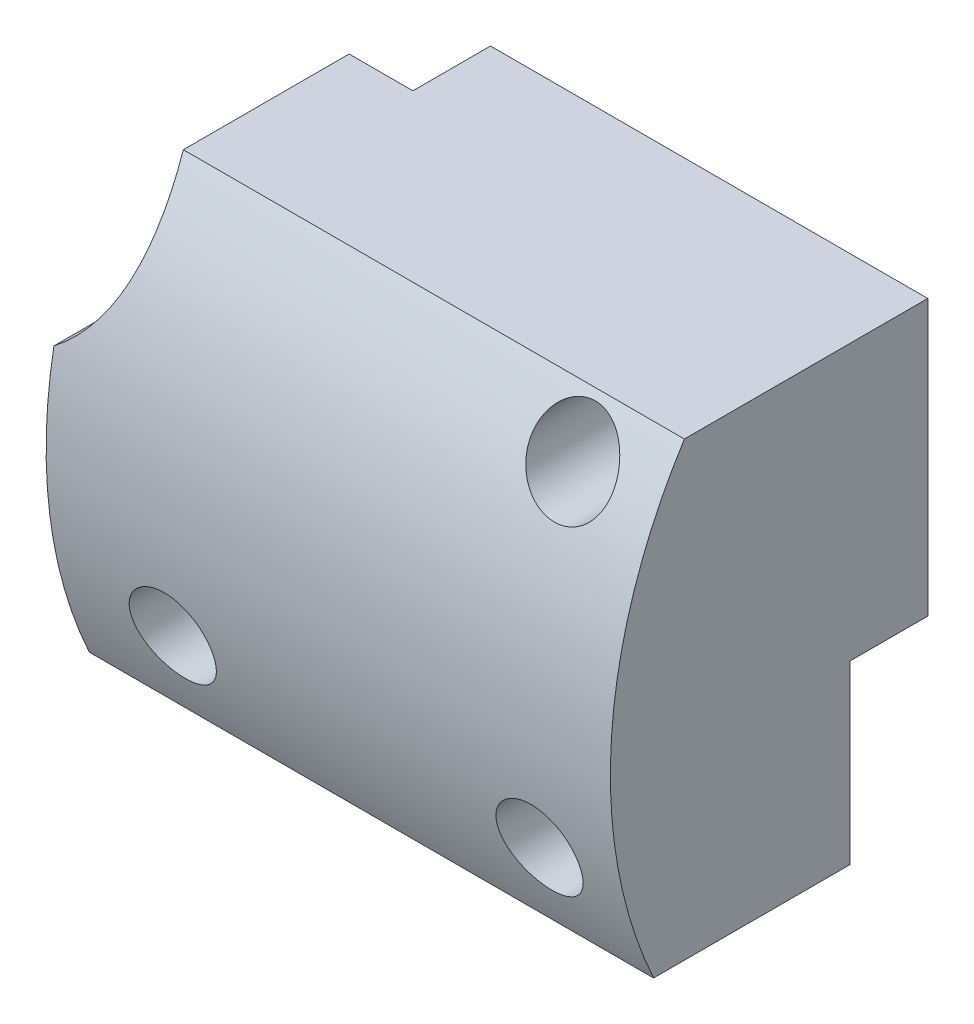
SolidWorks part; units mm, degrees
ref_plane "Front Plane" through (0, 0, 0) normal (0, 0, 1) x (1, 0, 0)
ref_plane "Top Plane" through (0, 0, 0) normal (0, 1, 0) x (1, 0, 0)
ref_plane "Right Plane" through (0, 0, 0) normal (1, 0, 0) x (0, 0, -1)
sketch "Sketch1" plane through (0, 0, 0) normal (0, 0, 1) x (1, 0, 0)
  line L1 (-21.3443, 32.2851) -> (-61.3443, 32.2851)
  line L2 (-21.3443, 32.2851) -> (-21.3443, 64.2851)
  line L3 (-21.3443, 64.2851) -> (-61.3443, 64.2851)
  line L4 (-61.3443, 32.2851) -> (-61.3443, 64.2851)
  dimension "D1" = 40
  dimension "D2" = 32
extrude "Boss-Extrude1" add sketch "Sketch1" along normal blind 17
sketch "Sketch3" plane through (0, 0, 0) normal (0, 0, -1) x (-1, 0, 0)
  line L1 (21.3443, 64.2851) -> (52.3443, 64.2851)
  line L2 (21.3443, 64.2851) -> (21.3443, 44.7851)
  line L3 (21.3443, 44.7851) -> (52.3443, 44.7851)
  line L4 (52.3443, 64.2851) -> (52.3443, 44.7851)
  dimension "D1" = 31
  dimension "D2" = 19.5
extrude "Boss-Extrude2" add sketch "Sketch3" along normal blind 5.5
sketch "Sketch2" plane through (0, 0, 17) normal (0, 0, 1) x (1, 0, 0)
  line L0 (-21.3443, 60.7851) -> (-61.3443, 60.7851) construction
  line L1 (-21.3443, 32.2851) -> (-21.3443, 64.2851) construction
  line L2 (-61.3443, 64.2851) -> (-61.3443, 32.2851) construction
  line L3 (-21.3443, 38.2851) -> (-61.3443, 38.2851) construction
  line L4 (-21.3443, 64.2851) -> (-61.3443, 64.2851) construction
  circle A0 centre (-27.3443, 60.7851) radius 1.75
  circle A1 centre (-27.3443, 38.2851) radius 1.75
  circle A2 centre (-53.3443, 38.2851) radius 1.75
  dimension "D1" = 3.5
  dimension "D2" = 6
  dimension "D3" = 26
  dimension "D4" = 22.5
  dimension "D5" = 3.5
extrude "Cut-Extrude1" cut sketch "Sketch2" against normal up to surface (22.5 mm away) up to face at (-36.8443, 54.5351, -5.5)
ref_plane "Plane1" through (-40.3443, 0, 0) normal (1, 0, 0) x (0, 0, -1)
sketch "Sketch4" plane through (-40.3443, 0, 0) normal (1, 0, 0) x (0, 0, -1)
  line L0 (-17, 64.2851) -> (5.5, 64.2851) construction
  line L1 (5.5, 64.2851) -> (5.5, 44.7851) construction
  line L2 (0.5, 57.2841) -> (11.5, 57.2841)
  line L3 (11.5, 46.2841) -> (11.5, 57.2841)
  arc A0 (0.5, 57.2841) -> (11.5, 46.2841) centre (0.5, 46.2841) ccw
  dimension "D1" = 18.001
  dimension "D2" = 5
extrude "Cut-Extrude2" cut sketch "Sketch4" against normal blind 6 and the other way blind 6
sketch "Sketch5" plane through (0, 0, -5.5) normal (0, 0, -1) x (-1, 0, 0)
  line L0 (40.3443, 12.375) -> (40.3443, -12.375) construction
  line L1 (34.3443, 57.2841) -> (46.3443, 57.2841) construction
  circle A0 centre (40.3443, 46.2841) radius 2.5
  dimension "D1" = 11
extrude "Cut-Extrude3" cut sketch "Sketch5" against normal offset from surface (21.5 mm away) 1 up to face at (-51.5943, 38.2851, 17)
sketch "Sketch6" plane through (0, 0, 17) normal (0, 0, 1) x (1, 0, 0)
  line L0 (-21.3443, 64.2851) -> (-61.3443, 64.2851) construction
  line L1 (-61.3443, 64.2851) -> (-61.3443, 32.2851) construction
  circle A0 centre (-68.3443, 61.7851) radius 11.75
  dimension "D1" = 23.5
  dimension "D2" = 2.5
  dimension "D3" = 7
extrude "Cut-Extrude4" cut sketch "Sketch6" against normal up to surface (22.5 mm away) up to face at (-38.5943, 52.7849, -5.5)
sketch "Sketch7" plane through (-40.3443, 0, 0) normal (1, 0, 0) x (0, 0, -1)
  line L0 (0.5, 46.2841) -> (3.5, 46.2841) construction
  line L1 (0.5, 50.7841) -> (3.5, 50.7841)
  line L2 (0.5, 41.7841) -> (3.5, 41.7841)
  arc A0 (0.5, 50.7841) -> (0.5, 41.7841) centre (0.5, 46.2841) ccw
  arc A1 (3.5, 41.7841) -> (3.5, 50.7841) centre (3.5, 46.2841) ccw
  point P3 (2, 46.2841)
  dimension "D1" = 4.5
  dimension "D2" = 3
extrude "Cut-Extrude5" cut sketch "Sketch7" against normal offset from surface 1 and the other way offset from surface (7 mm away) 1 up to face at (-46.3443, 47.9357, -0.1506) offset beyond the face yes other way up to face at (-34.3443, 47.9357, -0.1506)
sketch "Sketch9" plane through (0, 0, 17) normal (0, 0, 1) x (1, 0, 0)
  circle A1 centre (-27.3443, 38.2851) radius 3
  circle A2 centre (-53.3443, 38.2851) radius 3
  dimension "D1" = 6
extrude "Cut-Extrude7" cut sketch "Sketch9" against normal offset from surface (13 mm away) 4 up to face at (-51.5943, 38.2851, 0)
sketch "Sketch10" plane through (0, 0, 17) normal (0, 0, 1) x (1, 0, 0)
  circle A0 centre (-27.3443, 60.7851) radius 3
  dimension "D1" = 6
extrude "Cut-Extrude8" cut sketch "Sketch10" against normal offset from surface (18.5 mm away) 4 up to face at (-39.1776, 51.9617, -5.5)
sketch "Sketch8" plane through (-21.3443, 0, 0) normal (1, 0, 0) x (0, 0, -1)
  line L0 (0.5, 46.2841) -> (23.842, 46.2841) construction
  line L1 (-17, 32.2851) -> (-17, 64.2851) construction
  line L2 (-9.2618, 67.6986) -> (-19.6835, 67.6986)
  line L4 (-19.6835, 67.6986) -> (-19.6835, 31.0881)
  line L5 (-19.6835, 31.0881) -> (-13.3552, 31.0881)
  arc A0 (-9.2618, 67.6986) -> (-13.3552, 31.0881) centre (16.5, 46.2841) ccw
  dimension "D1" = 67
extrude "Cut-Extrude6" cut sketch "Sketch8" against normal up to surface (40 mm away) up to face at (-61.3443, 42.3165, 8.5)
